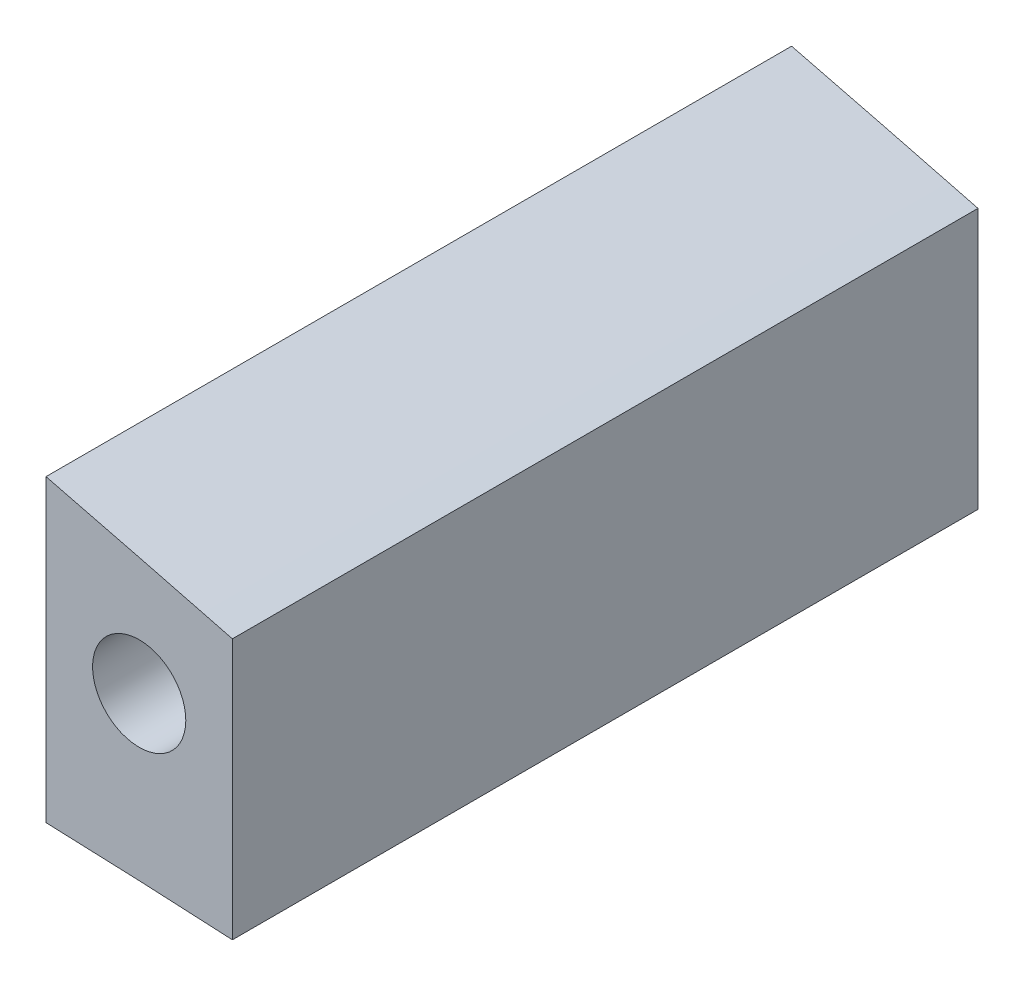
SolidWorks part; units mm, degrees
ref_plane "Front Plane" through (0, 0, 0) normal (0, 0, 1) x (1, 0, 0)
ref_plane "Top Plane" through (0, 0, 0) normal (0, 1, 0) x (1, 0, 0)
ref_plane "Right Plane" through (0, 0, 0) normal (1, 0, 0) x (0, 0, -1)
sketch "Sketch1" plane through (0, 0, 0) normal (0, 0, 1) x (1, 0, 0)
  spline S0 degree 3 poles (0.0006, 0.0001) (0.8106, 7.3592) (8.6491, 17.8566) (26.2867, 29.9752) (52.1111, 42.0692) (89.5976, 49.2908) (131.4008, 47.8848) (173.2567, 40.0411) (217.9611, 29.613) (256.9521, 19.5289) (290.3598, 8.711) (301.2732, 4.3828) (314.8169, -0.5162) (309.8463, 0.0001) knots 0 0 0 0 0.060864 0.113688 0.188609 0.312909 0.448482 0.557612 0.691544 0.852438 0.929756 0.976058 1 1 1 1
  spline S1 degree 3 poles (309.8463, 0.0001) (303.9568, 1.471) (293.9895, 2.094) (276.264, 4.5144) (260.8463, 5.4274) (235.8588, 7.8703) (205.1014, 8.8381) (157.7186, 9.0307) (110.4973, 6.1815) (66.5062, -0.5867) (36.4547, -6.0985) (15.3166, -6.1891) (1.2307, -6.9241) (0.0006, 0.0001) knots 0 0 0 0 0.057787 0.095275 0.171021 0.205339 0.335319 0.464904 0.658702 0.785512 0.893517 0.943092 1 1 1 1
extrude "Boss-Extrude1" add sketch "Sketch1" along normal blind 50.8
sketch "Sketch2" plane through (0, 0, 50.8) normal (0, 0, 1) x (1, 0, 0)
  circle A0 centre (20.32, 10.16) radius 6.35
  circle A1 centre (227.2963, 19.0501) radius 3.175
  dimension "D2" = 12.7
  dimension "D3" = 6.35
  dimension "D6" = 20.32
  dimension "D1" = 82.55
  dimension "D4" = 19.05
  dimension "D5" = 10.16
extrude "Cut-Extrude1" cut sketch "Sketch2" against normal through all
sketch "Sketch3" plane through (0, 0, 50.8) normal (0, 0, 1) x (1, 0, 0)
  line L1 (350.4863, -6.3499) -> (233.6463, -6.3499)
  line L2 (350.4863, -6.3499) -> (350.4863, 44.4501)
  line L3 (350.4863, 44.4501) -> (233.6463, 44.4501)
  line L4 (233.6463, -6.3499) -> (233.6463, 44.4501)
  circle A0 centre (227.2963, 19.0501) radius 3.175 construction
  dimension "D1" = 6.35
  dimension "D2" = 116.84
  dimension "D3" = 50.8
  dimension "D4" = 44.45
extrude "Cut-Extrude2" cut sketch "Sketch3" against normal through all contours L3 L4 L1 L2
sketch "Sketch4" plane through (0, 0, 50.8) normal (0, 0, 1) x (1, 0, 0)
  line L0 (233.6463, 7.6905) -> (233.6463, 25.4528) construction
  line L1 (220.9463, -24.2166) -> (-29.2042, -24.2166)
  line L2 (220.9463, -24.2166) -> (220.9463, 93.2727)
  line L3 (220.9463, 93.2727) -> (-29.2042, 93.2727)
  line L4 (-29.2042, -24.2166) -> (-29.2042, 93.2727)
  dimension "D1" = 12.7
extrude "Cut-Extrude3" cut sketch "Sketch4" against normal through all
